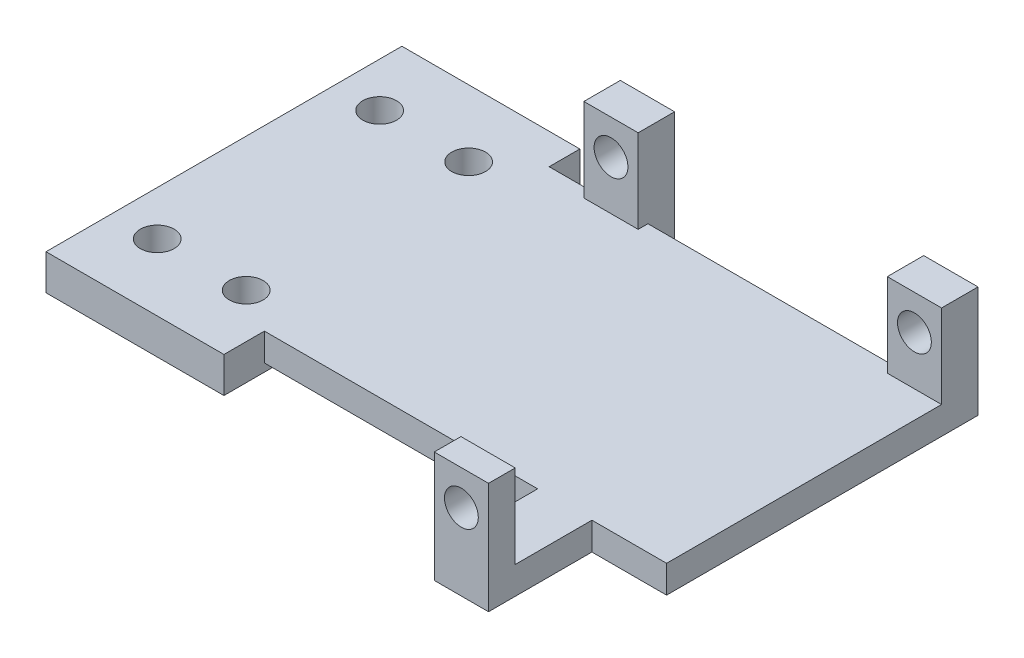
SolidWorks part; units mm, degrees
ref_plane "Front Plane" through (0, 0, 0) normal (0, 0, 1) x (1, 0, 0)
ref_plane "Top Plane" through (0, 0, 0) normal (0, 1, 0) x (1, 0, 0)
ref_plane "Right Plane" through (0, 0, 0) normal (1, 0, 0) x (0, 0, -1)
ref_plane "hole mount plane" through (0, 0, -30.905) normal (0, 0, -1) x (-1, 0, 0)
ref_plane "base rest" through (0, -5, 0) normal (0, -1, 0) x (-1, 0, 0)
sketch "Sketch2" plane through (0, -5, 0) normal (0, -1, 0) x (-1, 0, 0)
  line L0 (0, 16) -> (-10.4926, 16) construction
  line L1 (15, 0) -> (-60, 0)
  line L2 (15, 0) -> (15, 32)
  line L3 (15, 32) -> (-60, 32)
  line L4 (-60, 0) -> (-60, 32)
  line L5 (0, 0) -> (0, 32) construction
  line L6 (15, 32) -> (15, 0) construction
  dimension "D1" = 60
  dimension "D2" = 32
extrude "Boss-Extrude2" add sketch "Sketch2" against normal blind 3.1029 separate body
sketch "Sketch4" plane through (0, 0, -30.905) normal (0, 0, -1) x (-1, 0, 0)
  line L0 (15, -1.8971) -> (-60, -1.8971) construction
  line L1 (-11.1, -1.8971) -> (-5, -1.8971)
  line L2 (-11.1, -1.8971) -> (-11.1, 7.5029)
  line L3 (-11.1, 7.5029) -> (-5, 7.5029)
  line L4 (-5, -1.8971) -> (-5, 7.5029)
  line L5 (-8.05, 7.5029) -> (-8.05, -1.8971) construction
  line L6 (-8.05, 3.6029) -> (-42.15, 3.6029) construction
  line L7 (-42.15, 7.5029) -> (-42.15, -1.8971) construction
  line L8 (-45.2, -1.8971) -> (-45.2, 7.5029)
  line L9 (-39.1, 7.5029) -> (-45.2, 7.5029)
  line L10 (-39.1, -1.8971) -> (-39.1, 7.5029)
  line L11 (-39.1, -1.8971) -> (-45.2, -1.8971)
  line L12 (-60, -1.8971) -> (15, -1.8971) construction
  line L13 (0, 4) -> (0, -1.8971) construction
  circle A0 centre (-8.05, 3.6029) radius 1.9
  circle A1 centre (-42.15, 3.6029) radius 1.9
  dimension "D1" = 3.8
  dimension "D5" = 2
  dimension "D2" = 34.1
  dimension "D3" = 5.5
  dimension "D4" = 28
  dimension "D6" = 5
extrude "Boss-Extrude4" add sketch "Sketch4" along normal up to surface (1.095 mm away) up to face at (22.5, -3.4486, -32)
sketch "Sketch7" plane through (0, -1.8971, 0) normal (0, 1, 0) x (1, 0, 0)
  line L1 (60, 0) -> (45.2, 0)
  line L2 (60, 0) -> (60, 32)
  line L3 (60, 32) -> (45.2, 32)
  line L4 (45.2, 0) -> (45.2, 32)
extrude "trim" cut sketch "Sketch7" against normal through all
sketch "Sketch8" plane through (0, -1.8971, 0) normal (0, 1, 0) x (1, 0, 0)
  line L0 (33.76, 0) -> (33.76, -11.6219) construction
  line L1 (45.2, 0) -> (-15, 0) construction
  line L3 (30.71, -11.6219) -> (36.81, -11.6219)
  line L4 (30.71, -11.6219) -> (30.71, 0)
  line L5 (30.71, 0) -> (36.81, 0)
  line L6 (36.81, -11.6219) -> (36.81, 0)
  line L7 (45.2, 0) -> (-15, 0) construction
  line L8 (39.1, 32) -> (39.1, 30.905) construction
  dimension "D1" = 6.1
  dimension "D2" = 2.29
extrude "Boss-Extrude6" add sketch "Sketch8" against normal up to surface (3.1029 mm away) up to face at (15.1, -5, -16)
sketch "Sketch5" plane through (0, 0, 11.6219) normal (0, 0, 1) x (1, 0, 0)
  line L0 (60, -1.8971) -> (36.81, -1.8971) construction
  line L1 (30.71, -1.8971) -> (36.81, -1.8971)
  line L2 (30.71, -1.8971) -> (30.71, 7.5029)
  line L3 (30.71, 7.5029) -> (36.81, 7.5029)
  line L4 (36.81, -1.8971) -> (36.81, 7.5029)
  line L6 (33.76, 7.5029) -> (33.76, -1.8971) construction
  line L7 (33.76, 3.6029) -> (8.05, 3.6029) construction
  line L8 (5, 7.5029) -> (11.1, 7.5029) construction
  line L10 (39.1, -1.8971) -> (39.1, 7.5029) construction
  circle A0 centre (33.76, 3.6029) radius 1.9
  circle A1 centre (8.05, 3.6029) radius 1.9 construction
  dimension "D1" = 2.29
extrude "Boss-Extrude5" add sketch "Sketch5" against normal blind 3
sketch "Sketch9" plane through (0, 0, -32) normal (0, 0, -1) x (-1, 0, 0)
  line L0 (-45.2, 7.5029) -> (-39.1, 7.5029) construction
  line L1 (-39.1, 7.5029) -> (-39.1, -1.8971) construction
  line L2 (-11.1, -1.8971) -> (-11.1, 7.5029) construction
  line L3 (-11.1, 7.5029) -> (-5, 7.5029) construction
  line L4 (-5, 7.5029) -> (-5, -1.8971) construction
  line L5 (-45.2, 7.5029) -> (-39.1, 7.5029)
  line L6 (-39.1, 7.5029) -> (-39.1, -1.8971)
  line L7 (-11.1, -1.8971) -> (-11.1, 7.5029)
  line L8 (-11.1, 7.5029) -> (-5, 7.5029)
  line L9 (-5, 7.5029) -> (-5, -1.8971)
  line L10 (-45.2, 7.5029) -> (-45.2, -5)
  line L11 (-45.2, -5) -> (-39.1, -5)
  line L12 (15, -5) -> (-45.2, -5) construction
  line L13 (-39.1, -5) -> (-39.1, -1.8971)
  line L14 (-11.1, -1.8971) -> (-11.1, -5)
  line L15 (-11.1, -5) -> (-5, -5)
  line L16 (-5, -5) -> (-5, -1.8971)
  circle A0 centre (-42.15, 3.6029) radius 1.9 construction
  circle A1 centre (-8.05, 3.6029) radius 1.9 construction
  circle A2 centre (-42.15, 3.6029) radius 1.9
  circle A3 centre (-8.05, 3.6029) radius 1.9
extrude "Boss-Extrude8" add sketch "Sketch9" along normal blind 3
sketch "Sketch10" plane through (0, -1.8971, 0) normal (0, 1, 0) x (1, 0, 0)
  line L1 (-20, 35.4525) -> (0, 35.4525)
  line L2 (-20, 35.4525) -> (-20, -4.5475)
  line L3 (-20, -4.5475) -> (0, -4.5475)
  line L4 (0, 35.4525) -> (0, -4.5475)
  line L5 (45.2, 15.4525) -> (-15, 15.4525) construction
  line L6 (45.2, 30.905) -> (45.2, 0) construction
  line L7 (-15, 0) -> (-15, 32) construction
  dimension "D3" = 5
  dimension "D1" = 40
  dimension "D2" = 20
extrude "Boss-Extrude9" add sketch "Sketch10" against normal blind 4
sketch "Sketch11" plane through (0, -1.8971, 0) normal (0, 1, 0) x (1, 0, 0)
  line L0 (-20, 15.4525) -> (45.2, 15.4525) construction
  line L3 (-10, 35.4525) -> (-10, -4.5475) construction
  line L4 (0, 35.4525) -> (-20, 35.4525) construction
  line L5 (-20, -4.5475) -> (0, -4.5475) construction
  line L6 (-20, 35.4525) -> (-20, -4.5475) construction
  line L7 (45.2, 30.905) -> (45.2, 0) construction
  circle A0 centre (-15, 27.9525) radius 1.9
  circle A1 centre (-5, 27.9525) radius 1.9
  circle A2 centre (-15, 2.9525) radius 1.9
  circle A3 centre (-5, 2.9525) radius 1.9
  dimension "D1" = 3.8
  dimension "D2" = 10
  dimension "D3" = 25
extrude "Cut-Extrude2" cut sketch "Sketch11" against normal blind 4
